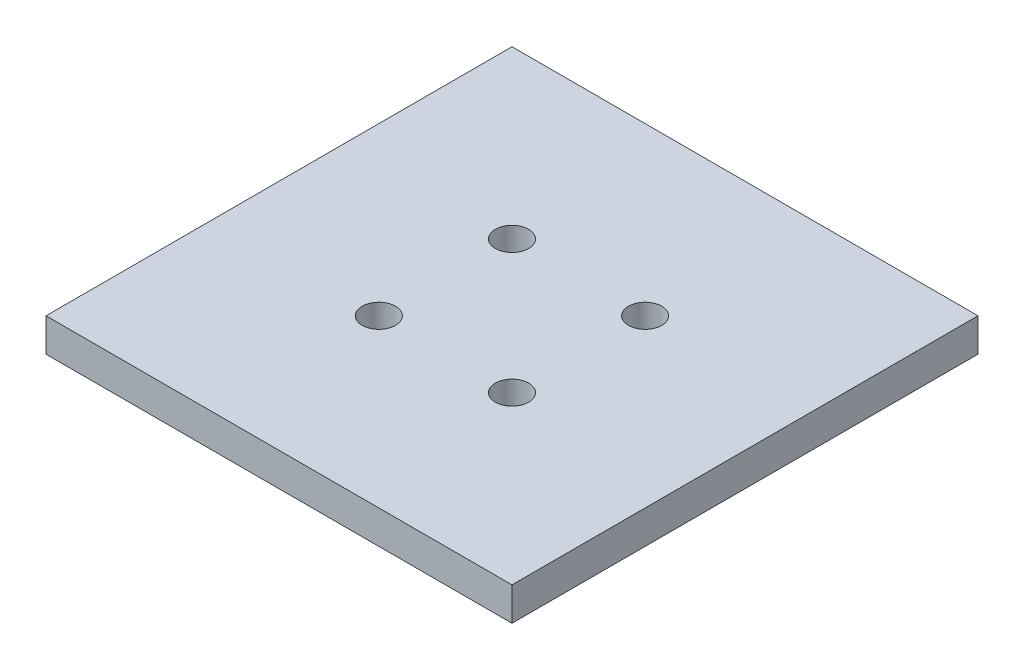
SolidWorks part; units mm, degrees
ref_plane "Front Plane" through (0, 0, 0) normal (0, 0, 1) x (1, 0, 0)
ref_plane "Top Plane" through (0, 0, 0) normal (0, 1, 0) x (1, 0, 0)
ref_plane "Right Plane" through (0, 0, 0) normal (1, 0, 0) x (0, 0, -1)
sketch "Sketch1" plane through (0, 0, 0) normal (0, 1, 0) x (1, 0, 0)
  line L1 (-44.45, -44.45) -> (44.45, -44.45)
  line L2 (-44.45, -44.45) -> (-44.45, 44.45)
  line L3 (-44.45, 44.45) -> (44.45, 44.45)
  line L4 (44.45, -44.45) -> (44.45, 44.45)
  line L5 (-44.45, -44.45) -> (44.45, 44.45) construction
  line L6 (-44.45, 44.45) -> (44.45, -44.45) construction
  line L7 (-12.7, -12.7) -> (12.7, -12.7) construction
  line L8 (-12.7, -12.7) -> (-12.7, 12.7) construction
  line L9 (-12.7, 12.7) -> (12.7, 12.7) construction
  line L10 (12.7, -12.7) -> (12.7, 12.7) construction
  line L11 (-12.7, -12.7) -> (12.7, 12.7) construction
  line L12 (-12.7, 12.7) -> (12.7, -12.7) construction
  circle A1 centre (12.7, 12.7) radius 3.175
  circle A2 centre (12.7, -12.7) radius 3.175
  circle A3 centre (-12.7, -12.7) radius 3.175
  circle A4 centre (-12.7, 12.7) radius 3.175
  point P0 (0, 0)
  point P6 (0, 0)
  dimension "D2" = 6.35
  dimension "D1" = 88.9
  dimension "D3" = 25.4
extrude "Boss-Extrude1" add sketch "Sketch1" along normal blind 6.35
